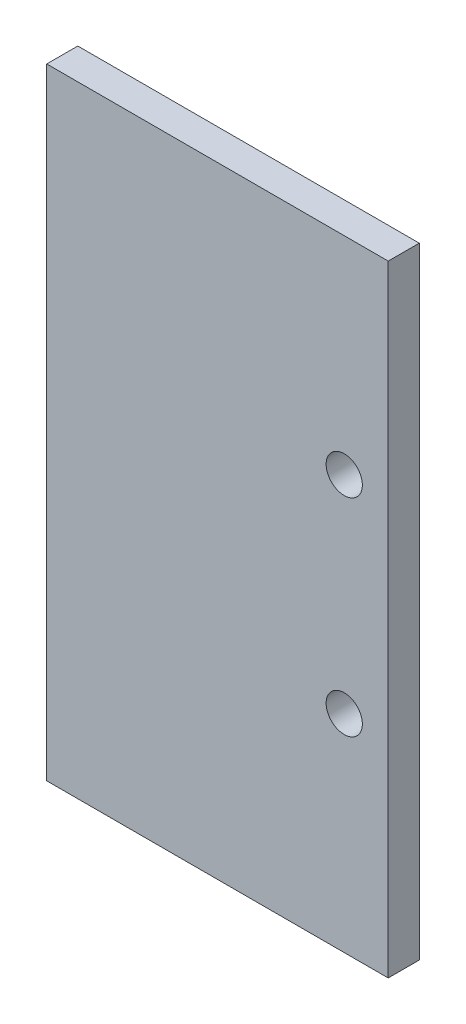
SolidWorks part; units mm, degrees
ref_plane "Plan de face" through (0, 0, 0) normal (0, 0, 1) x (1, 0, 0)
ref_plane "Plan de dessus" through (0, 0, 0) normal (0, 1, 0) x (1, 0, 0)
ref_plane "Plan de droite" through (0, 0, 0) normal (1, 0, 0) x (0, 0, -1)
sketch "Esquisse1" plane through (0, 0, 0) normal (0, 0, 1) x (1, 0, 0)
  line L1 (0, 0) -> (33, 0)
  line L2 (0, 0) -> (0, 60)
  line L3 (0, 60) -> (33, 60)
  line L4 (33, 0) -> (33, 60)
  dimension "D1" = 60
  dimension "D2" = 33
extrude "Boss.-Extru.1" add sketch "Esquisse1" along normal blind 3
sketch "Esquisse3" plane through (0, 0, 0) normal (0, 0, -1) x (-1, 0, 0)
  line L0 (-3.75, 53) -> (-3.75, 7) construction
  line L1 (-3.75, 30) -> (0, 30) construction
  line L2 (0, 60) -> (0, 0) construction
  circle A0 centre (-3.75, 53) radius 3.75
  circle A1 centre (-3.75, 7) radius 3.75
  dimension "D2" = 7.5
  dimension "D1" = 46
extrude "Boss.-Extru.2" add sketch "Esquisse3" along normal blind 1.2
sketch "Esquisse4" plane through (0, 0, 0) normal (0, 0, -1) x (-1, 0, 0)
  line L0 (-28.75, 40) -> (-28.75, 20) construction
  line L1 (-28.75, 30) -> (-33, 30) construction
  line L2 (-33, 0) -> (-33, 60) construction
  circle A0 centre (-28.75, 40) radius 1.75
  circle A1 centre (-28.75, 20) radius 1.75
  circle A2 centre (-3.75, 53) radius 3.75 construction
  dimension "D2" = 3.5
  dimension "D3" = 25
  dimension "D1" = 20
extrude "Enlèv. mat.-Extru.1" cut sketch "Esquisse4" against normal through all
